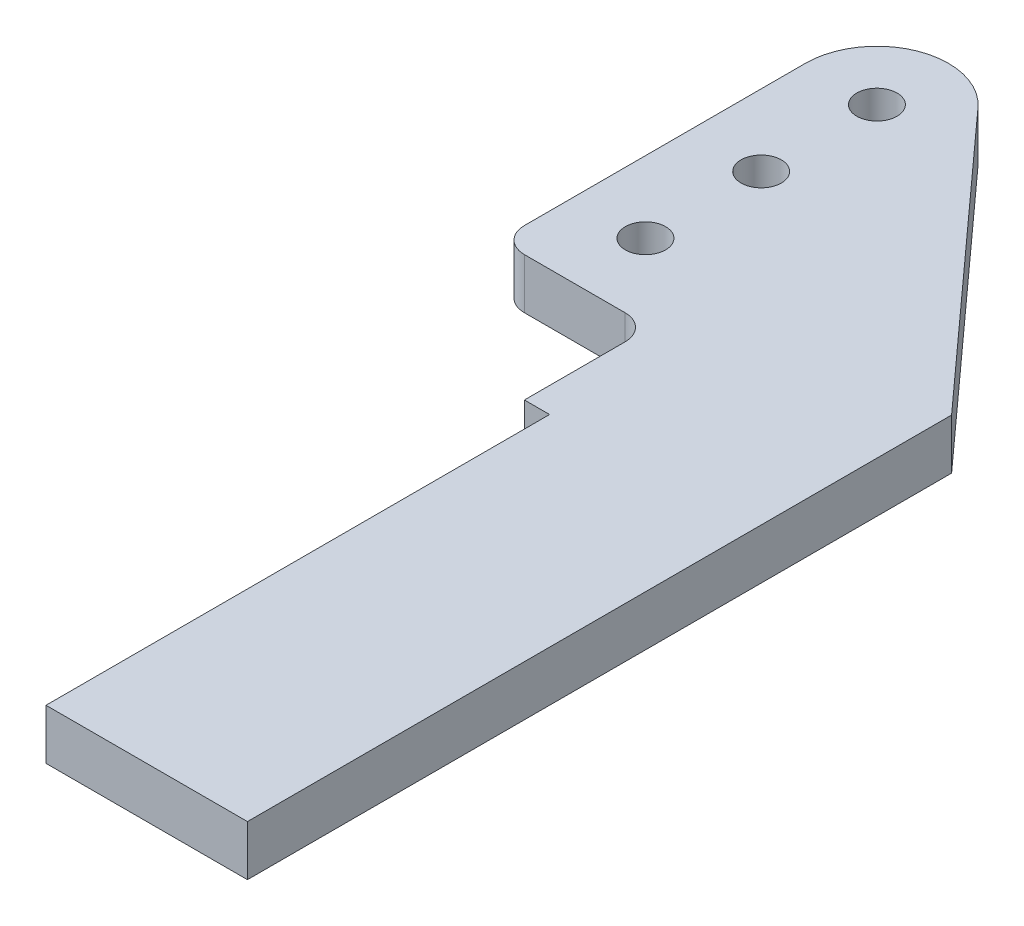
SolidWorks part; units mm, degrees
ref_plane "Front" through (0, 0, 0) normal (0, 0, 1) x (1, 0, 0)
ref_plane "Top" through (0, 0, 0) normal (0, 1, 0) x (1, 0, 0)
ref_plane "Right" through (0, 0, 0) normal (1, 0, 0) x (0, 0, -1)
sketch "Sketch1" plane through (0, 0, 0) normal (0, 1, 0) x (1, 0, 0)
  line L0 (0, 1) -> (0, 12.158)
  line L1 (4.9486, 14.0656) -> (15, 2.9653)
  line L2 (15, 2.9653) -> (15, -25)
  line L3 (15, -25) -> (7, -25)
  line L4 (7, -25) -> (7, -5)
  line L5 (1, 0) -> (5, 0)
  line L6 (2.842, 7.5617) -> (2.842, 2.9653) construction
  line L7 (2.842, 7.5617) -> (2.842, 2.9653) construction
  line L8 (2.842, 12.158) -> (2.842, 7.5617) construction
  line L9 (7, -5) -> (15, -5) construction
  line L10 (7, -5) -> (6, -5)
  line L11 (6, -5) -> (6, -1)
  arc A0 (0, 12.158) -> (4.9486, 14.0656) centre (2.842, 12.158) cw
  circle A1 centre (2.842, 7.5617) radius 0.8
  circle A2 centre (2.842, 2.9653) radius 0.8
  circle A3 centre (2.842, 7.5617) radius 0.8
  arc A4 (1, 0) -> (0, 1) centre (1, 1) cw
  circle A6 centre (2.842, 12.158) radius 0.8
  arc A7 (5, 0) -> (6, -1) centre (5, -1) cw
  point P10 (6, 0)
  point P17 (0, 0)
  point P19 (5.1048, -5)
  point P22 (2.842, 7.5617)
  point P24 (18, 2.9653)
  dimension "D1" = 1.6
  dimension "D3" = 1
  dimension "D4" = 40
  dimension "D7" = 1
  dimension "D2" = 15
  dimension "D5" = 25
  dimension "D6" = 5
  dimension "D8" = 8
  dimension "D9" = 1
extrude "Boss-Extrude1" add sketch "Sketch1" along normal blind 2 contours L5 A7 L11 L10 L4 L3 L2 L1 A0 L0 A4 A1 A2 A6
